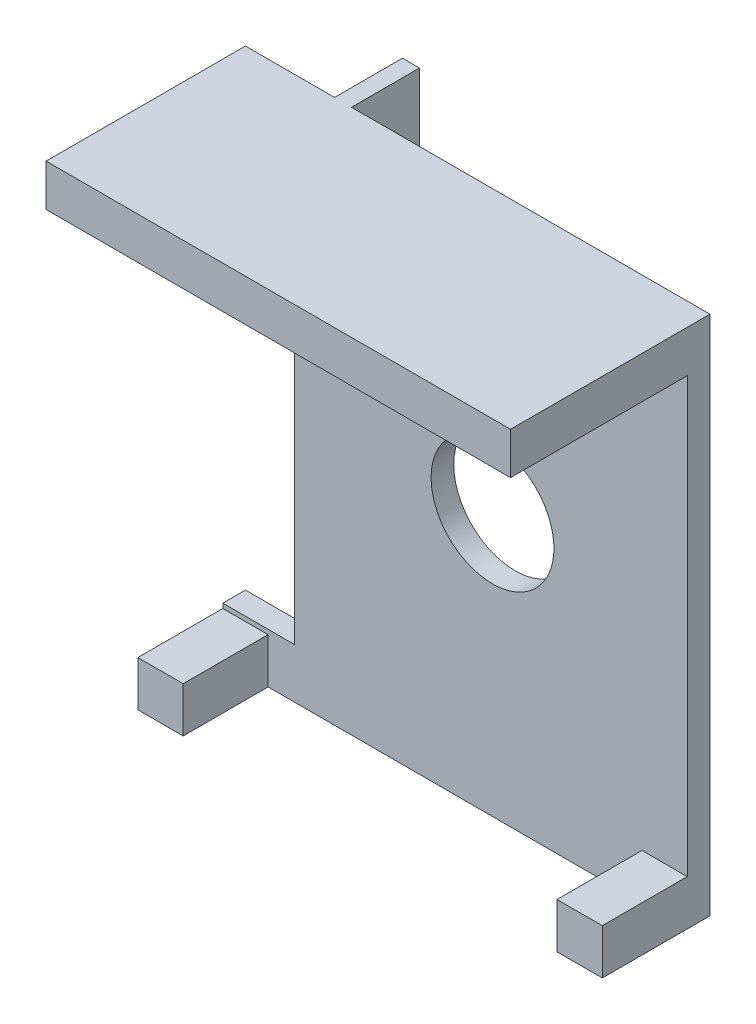
SolidWorks part; units mm, degrees
ref_plane "Piano frontale" through (0, 0, 0) normal (0, 0, 1) x (1, 0, 0)
ref_plane "Piano superiore" through (0, 0, 0) normal (0, 1, 0) x (1, 0, 0)
ref_plane "Piano destro" through (0, 0, 0) normal (1, 0, 0) x (0, 0, -1)
sketch "Schizzo1" plane through (0, 0, 0) normal (0, 0, 1) x (1, 0, 0)
  line L1 (0, 0) -> (41, 0)
  line L2 (0, 0) -> (0, 46)
  line L3 (0, 46) -> (41, 46)
  line L4 (41, 0) -> (41, 46)
  dimension "D1" = 41
  dimension "D2" = 46
extrude "Estrusione-Estrusione1" add sketch "Schizzo1" along normal blind 2
sketch "Schizzo2" plane through (0, 0, 2) normal (0, 0, 1) x (1, 0, 0)
  line L1 (0, 0) -> (4, 0)
  line L2 (0, 0) -> (0, 4)
  line L3 (0, 4) -> (4, 4)
  line L4 (4, 0) -> (4, 4)
  line L5 (41, 0) -> (37, 0)
  line L6 (41, 0) -> (41, 4)
  line L7 (41, 4) -> (37, 4)
  line L8 (37, 0) -> (37, 4)
  dimension "D1" = 4
  dimension "D2" = 4
  dimension "D3" = 4
  dimension "D4" = 4
extrude "Estrusione-Estrusione2" add sketch "Schizzo2" along normal blind 7.5
sketch "Schizzo3" plane through (0, 0, 2) normal (0, 0, 1) x (1, 0, 0)
  line L0 (41, 4) -> (41, 46) construction
  line L1 (0, 46) -> (41, 46)
  line L2 (0, 46) -> (0, 42.3)
  line L3 (0, 42.3) -> (41, 42.3)
  line L4 (41, 46) -> (41, 42.3)
  dimension "D1" = 3.7
extrude "Estrusione-Estrusione3" add sketch "Schizzo3" along normal blind 15.6
sketch "Schizzo4" plane through (0, 0, 0) normal (0, 0, -1) x (-1, 0, 0)
  line L0 (0, 46) -> (0, 0) construction
  line L1 (0, 38.7495) -> (-6.3157, 38.7495)
  line L2 (0, 38.7495) -> (0, 4.408)
  line L3 (0, 4.408) -> (-6.3157, 4.408)
  line L4 (-6.3157, 38.7495) -> (-6.3157, 4.408)
extrude "Taglio-Estrusione1" cut sketch "Schizzo4" against normal blind 2
sketch "Schizzo5" plane through (0, 0, 0) normal (0, 0, -1) x (-1, 0, 0)
  line L0 (-41, 46) -> (0, 46) construction
  line L1 (-9.3615, 46) -> (-7.8615, 46)
  line L2 (-9.3615, 46) -> (-9.3615, 32)
  line L3 (-9.3615, 32) -> (-7.8615, 32)
  line L4 (-7.8615, 46) -> (-7.8615, 32)
  dimension "D1" = 1.5
  dimension "D2" = 14
extrude "Estrusione-Estrusione4" add sketch "Schizzo5" along normal blind 6
sketch "Schizzo7" plane through (0, 0, 0) normal (0, 0, -1) x (-1, 0, 0)
  circle A0 centre (-23.8074, 23.2055) radius 5.422
extrude "Taglio-Estrusione3" cut sketch "Schizzo7" against normal blind 2
